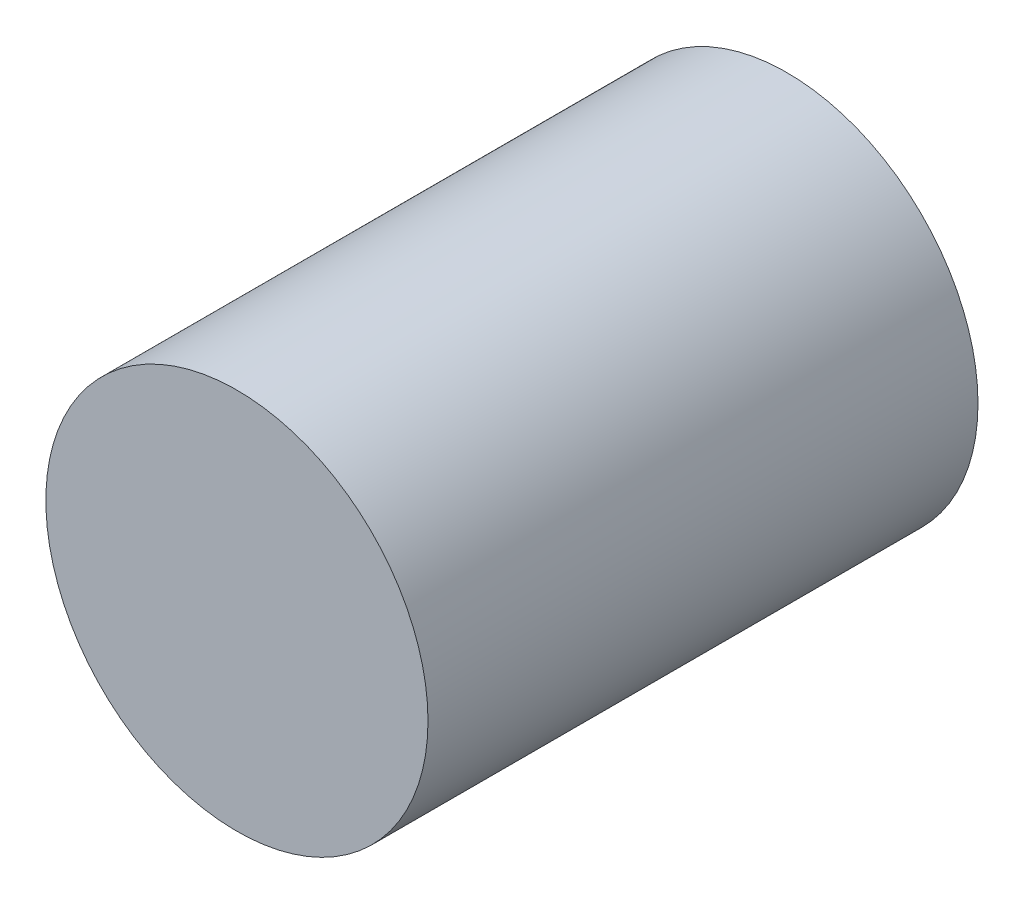
SolidWorks part; units mm, degrees
ref_plane "前视基准面" through (0, 0, 0) normal (0, 0, 1) x (1, 0, 0)
ref_plane "上视基准面" through (0, 0, 0) normal (0, 1, 0) x (1, 0, 0)
ref_plane "右视基准面" through (0, 0, 0) normal (1, 0, 0) x (0, 0, -1)
sketch "草图1" plane through (0, 0, 0) normal (0, 0, 1) x (1, 0, 0)
  circle A0 centre (-41.0091, 15.2405) radius 7.2957
extrude "凸台-拉伸1" add sketch "草图1" along normal blind 21
